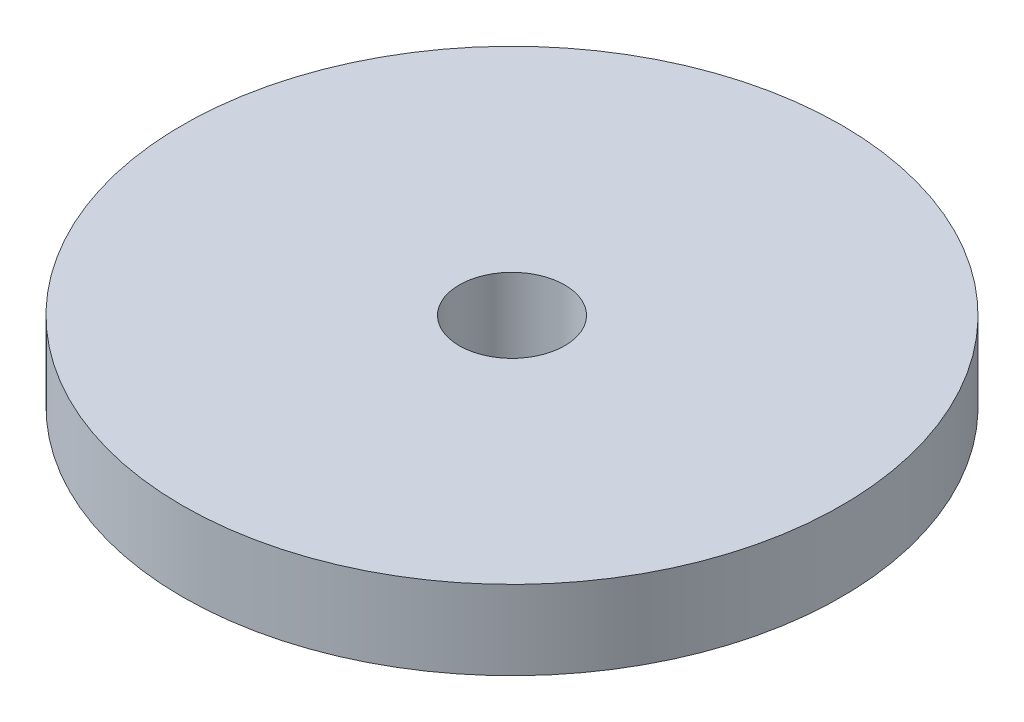
SolidWorks part; units mm, degrees
ref_plane "Front Plane" through (0, 0, 0) normal (0, 0, 1) x (1, 0, 0)
ref_plane "Top Plane" through (0, 0, 0) normal (0, 1, 0) x (1, 0, 0)
ref_plane "Right Plane" through (0, 0, 0) normal (1, 0, 0) x (0, 0, -1)
sketch "Sketch1" plane through (0, 0, 0) normal (0, 1, 0) x (1, 0, 0)
  circle A0 centre (0, 0) radius 2
  circle A1 centre (0, 0) radius 12.5
  dimension "D1" = 25
  dimension "D2" = 4
extrude "Boss-Extrude1" add sketch "Sketch1" along normal blind 3
